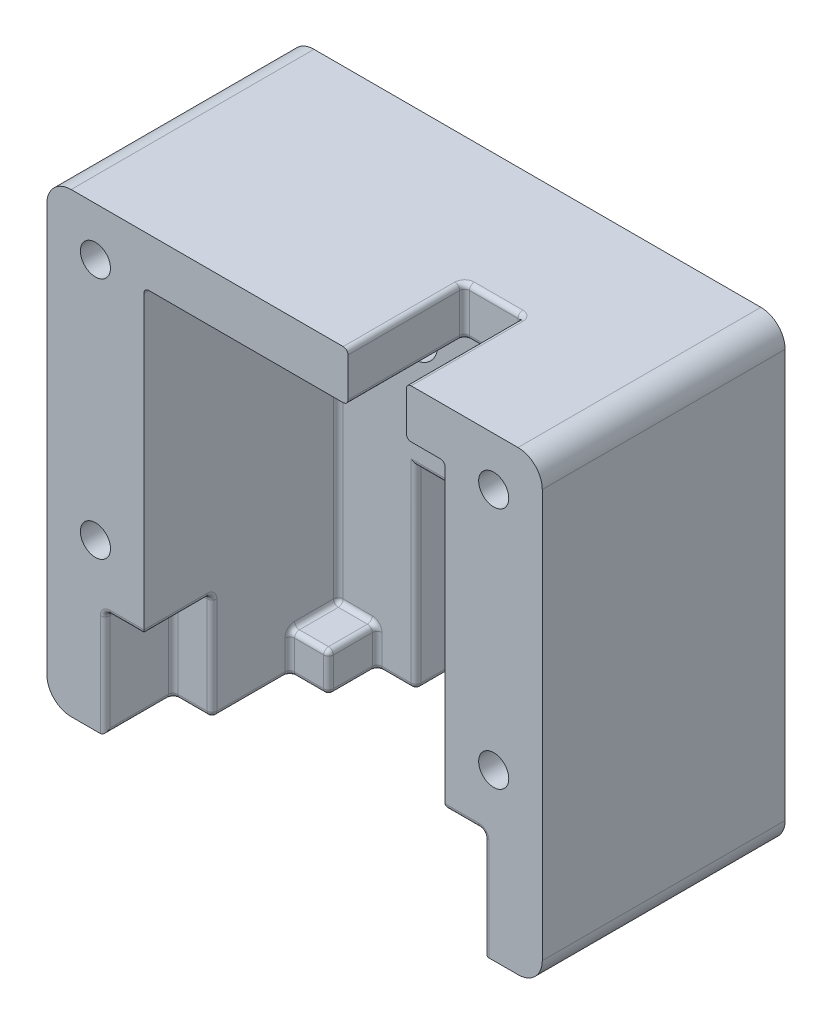
SolidWorks part; units mm, degrees
ref_plane "Front Plane" through (0, 0, 0) normal (0, 0, 1) x (1, 0, 0)
ref_plane "Top Plane" through (0, 0, 0) normal (0, 1, 0) x (1, 0, 0)
ref_plane "Right Plane" through (0, 0, 0) normal (1, 0, 0) x (0, 0, -1)
sketch "Sketch1" plane through (0, 0, 0) normal (0, 0, 1) x (1, 0, 0)
  line L0 (0, 0) -> (51, 0)
  line L1 (51, 0) -> (51, 47)
  line L2 (51, 47) -> (0, 47)
  line L3 (0, 47) -> (0, 0)
  dimension "D1" = 51
  dimension "D2" = 47
extrude "Boss-Extrude1" add sketch "Sketch1" along normal blind 5
sketch "Sketch2" plane through (0, 0, 5) normal (0, 0, 1) x (1, 0, 0)
  line L0 (0, 0) -> (0, 47)
  line L1 (0, 47) -> (51, 47)
  line L2 (51, 47) -> (51, 0)
  line L3 (51, 0) -> (41, 0)
  line L4 (0, 0) -> (51, 0) construction
  line L5 (41, 0) -> (41, 42)
  line L6 (41, 42) -> (10, 42)
  line L7 (10, 42) -> (10, 0)
  line L8 (10, 0) -> (0, 0)
  dimension "D1" = 10
  dimension "D2" = 10
  dimension "D3" = 5
extrude "Boss-Extrude2" add sketch "Sketch2" along normal blind 20
sketch "Sketch4" plane through (0, 0, 5) normal (0, 0, 1) x (1, 0, 0)
  line L0 (41, 0) -> (37, 0)
  line L1 (10, 0) -> (41, 0) construction
  line L2 (37, 0) -> (37, 4)
  line L3 (37, 4) -> (41, 4)
  line L4 (41, 42) -> (41, 0) construction
  line L5 (41, 4) -> (41, 0)
  line L6 (10, 0) -> (14, 0)
  line L7 (14, 0) -> (14, 4)
  line L8 (14, 4) -> (10, 4)
  line L9 (10, 0) -> (10, 42) construction
  line L10 (10, 4) -> (10, 0)
  dimension "D1" = 4
  dimension "D2" = 4
  dimension "D3" = 4
  dimension "D4" = 4
extrude "Boss-Extrude3" add sketch "Sketch4" along normal blind 5
sketch "Sketch5" plane through (0, 0, 25) normal (0, 0, 1) x (1, 0, 0)
  line L0 (41, 0) -> (41, 11)
  line L1 (41, 42) -> (41, 4) construction
  line L2 (41, 11) -> (45, 11)
  line L3 (45, 11) -> (45, 0)
  line L4 (41, 0) -> (51, 0) construction
  line L5 (45, 0) -> (41, 0)
  line L6 (10, 0) -> (10, 11)
  line L7 (10, 4) -> (10, 42) construction
  line L8 (10, 11) -> (6, 11)
  line L9 (6, 11) -> (6, 0)
  line L10 (0, 0) -> (10, 0) construction
  line L11 (6, 0) -> (10, 0)
  dimension "D1" = 4
  dimension "D2" = 11
  dimension "D3" = 11
  dimension "D4" = 4
extrude "Cut-Extrude1" cut sketch "Sketch5" against normal blind 7
sketch "Sketch7" plane through (0, 0, 25) normal (0, 0, 1) x (1, 0, 0)
  line L0 (37, 47) -> (37, 42)
  line L1 (51, 47) -> (0, 47) construction
  line L2 (10, 42) -> (41, 42) construction
  line L3 (37, 42) -> (31, 42)
  line L4 (10, 42) -> (41, 42) construction
  line L5 (31, 42) -> (31, 47)
  line L6 (31, 47) -> (37, 47)
  line L7 (41, 42) -> (41, 11) construction
  dimension "D1" = 4
  dimension "D2" = 6
extrude "Cut-Extrude2" cut sketch "Sketch7" against normal blind 12
sketch "Sketch8" plane through (0, 0, 5) normal (0, 0, 1) x (1, 0, 0)
  line L0 (25.5, 0) -> (33, 0)
  line L1 (14, 0) -> (37, 0) construction
  line L2 (33, 0) -> (33, 20)
  line L3 (33, 20) -> (18, 20)
  line L4 (18, 20) -> (18, 0)
  line L5 (18, 0) -> (25.5, 0)
  dimension "D1" = 7.5
  dimension "D2" = 7.5
  dimension "D3" = 20
extrude "Cut-Extrude3" cut sketch "Sketch8" against normal blind 4
sketch "Sketch9" plane through (0, 0, 25) normal (0, 0, 1) x (1, 0, 0)
  line L0 (0, 47) -> (0, 0) construction
  line L1 (31, 47) -> (0, 47) construction
  line L2 (51, 47) -> (37, 47) construction
  line L3 (51, 0) -> (51, 47) construction
  circle A0 centre (5, 17) radius 1.55
  circle A1 centre (5, 42) radius 1.55
  circle A2 centre (46, 42) radius 1.55
  circle A3 centre (46, 17) radius 1.55
  dimension "D1" = 3.1
  dimension "D2" = 3.1
  dimension "D3" = 3.1
  dimension "D4" = 3.1
  dimension "D5" = 25
  dimension "D6" = 25
  dimension "D7" = 5
  dimension "D8" = 5
  dimension "D9" = 5
  dimension "D10" = 5
extrude "Cut-Extrude4" cut sketch "Sketch9" against normal blind 10
sketch "Sketch10" plane through (0, 0, 5) normal (0, 0, 1) x (1, 0, 0)
  line L0 (10, 4) -> (10, 42) construction
  line L2 (41, 42) -> (41, 4) construction
  line L3 (10, 42) -> (41, 42) construction
  circle A0 centre (17.75, 32) radius 1.75
  circle A1 centre (33.25, 32) radius 1.75
  point P4 (0, 0)
  dimension "D1" = 3.5
  dimension "D2" = 3.5
  dimension "D3" = 7.75
  dimension "D4" = 7.75
  dimension "D5" = 10
extrude "Cut-Extrude5" cut sketch "Sketch10" against normal through all
sketch "Sketch11" plane through (0, 0, 5) normal (0, 0, 1) x (1, 0, 0)
  circle A0 centre (17.75, 32) radius 2.5
  circle A1 centre (33.25, 32) radius 2.5
  dimension "D1" = 5
  dimension "D2" = 5
extrude "Cut-Extrude6" cut sketch "Sketch11" against normal blind 2
fillet "Fillet1" radius 0.5 62 edges at (10, 4, 7.5) (10, 0, 14) (6, 0, 21.5) (18, 0, 3) (33, 0, 3) (41, 4, 7.5) (45, 0, 21.5) (37, 42, 19) (37, 47, 19) (31, 42, 19) (31, 47, 19) (10, 11, 21.5) (6, 11, 21.5) (8, 11, 25) (45, 11, 21.5) (41, 11, 21.5) (43, 11, 25) (14, 0, 7.5) (14, 4, 7.5) (12, 4, 10) (14, 2, 10) (12, 0, 10) (10, 2, 10) (6, 5.5, 18) (8, 11, 18) (10, 5.5, 18) (8, 0, 18) (16, 0, 5) (14, 2, 5) (12, 4, 5) (10, 23, 5) (25.5, 42, 5) (41, 23, 5) (39, 4, 5) (35, 0, 5) (33, 10, 5) (25.5, 20, 5) (18, 10, 5) (18, 10, 1) (25.5, 20, 1) (33, 10, 1) (25.5, 0, 1) (37, 4, 7.5) (37, 0, 7.5) (37, 2, 5) (39, 0, 10) (37, 2, 10) (39, 4, 10) (41, 2, 10) (41, 5.5, 18) (43, 11, 18) (45, 5.5, 18) (43, 0, 18) (37, 44.5, 13) (34, 42, 13) (31, 44.5, 13) (34, 47, 13) (41, 42, 15) (10, 42, 15) (41, 0, 14) (45, 5.5, 25) (6, 5.5, 25)
fillet "Fillet2" radius 2.5 4 edges at (0, 47, 12.5) (51, 47, 12.5) (51, 0, 12.5) (0, 0, 12.5)
